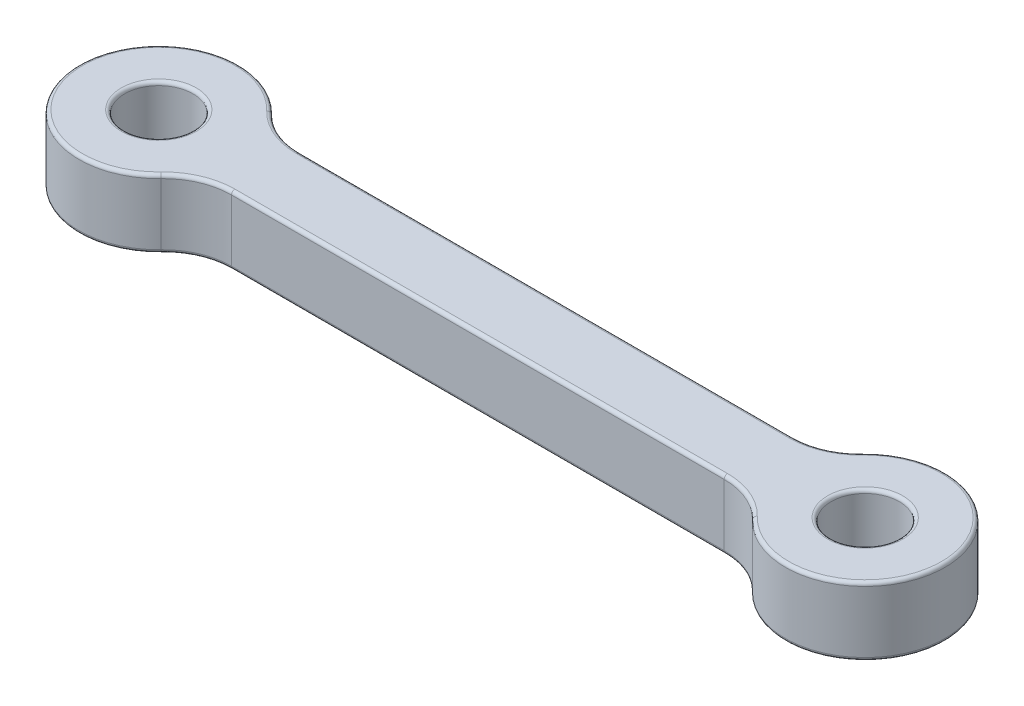
SolidWorks part; units mm, degrees
ref_plane "Front Plane" through (0, 0, 0) normal (0, 0, 1) x (1, 0, 0)
ref_plane "Top Plane" through (0, 0, 0) normal (0, 1, 0) x (1, 0, 0)
ref_plane "Right Plane" through (0, 0, 0) normal (1, 0, 0) x (0, 0, -1)
sketch "Sketch1" plane through (0, 0, 0) normal (0, 1, 0) x (1, 0, 0)
  line L0 (-15.5, 0) -> (15.5, 0) construction
  line L1 (-15.5, 3.5) -> (15.5, 3.5) construction
  line L2 (-15.5, -3.5) -> (15.5, -3.5) construction
  line L3 (0, 0) -> (0, -3.5) construction
  line L5 (12.3377, 1.5) -> (-12.3377, 1.5)
  line L6 (12.3377, 1.5) -> (12.3377, -1.5) construction
  line L7 (12.3377, -1.5) -> (-12.3377, -1.5)
  line L8 (-12.3377, 1.5) -> (-12.3377, -1.5) construction
  line L9 (12.3377, 1.5) -> (-12.3377, -1.5) construction
  line L10 (12.3377, -1.5) -> (-12.3377, 1.5) construction
  arc A0 (-15.5, 3.5) -> (-15.5, -3.5) centre (-15.5, 0) ccw construction
  arc A1 (15.5, -3.5) -> (15.5, 3.5) centre (15.5, 0) ccw construction
  circle A2 centre (-15.5, 0) radius 3.5
  circle A3 centre (-15.5, 0) radius 1.5
  circle A6 centre (15.5, 0) radius 1.5
  circle A7 centre (15.5, 0) radius 3.5
  point P2 (0, 0)
  dimension "D3" = 3
  dimension "D4" = 3
  dimension "D1" = 31
  dimension "D2" = 7
extrude "Boss-Extrude1" add sketch "Sketch1" along normal mid plane 3 contours A2 A3 | L7 A7 L5 A2 | A7 A6
fillet "Fillet1" radius 3 4 edges at (-12.3377, 0, -1.5) (-12.3377, 0, 1.5) (12.3377, 0, -1.5) (12.3377, 0, 1.5)
fillet "Fillet2" radius 0.15 20 edges at (15.5, -1.5, 1.5) (-11.9863, -1.5, 1.7404) (0, -1.5, 1.5) (11.9863, -1.5, 1.7404) (19, -1.5, 0) (11.9863, -1.5, -1.7404) (0, -1.5, -1.5) (-11.9863, -1.5, -1.7404) (-19, -1.5, 0) (-15.5, -1.5, 1.5) (15.5, 1.5, 1.5) (11.9863, 1.5, -1.7404) (19, 1.5, 0) (11.9863, 1.5, 1.7404) (0, 1.5, 1.5) (-11.9863, 1.5, 1.7404) (-19, 1.5, 0) (-11.9863, 1.5, -1.7404) (0, 1.5, -1.5) (-15.5, 1.5, 1.5)
